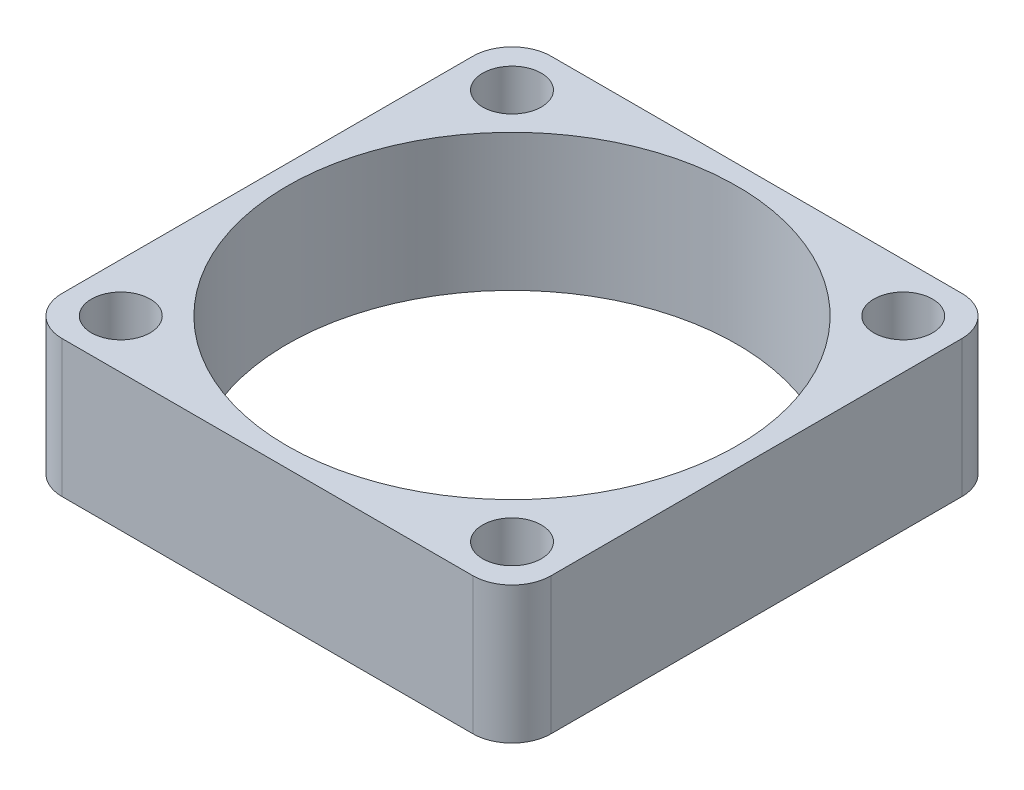
SolidWorks part; units mm, degrees
ref_plane "前视基准面" through (0, 0, 0) normal (0, 0, 1) x (1, 0, 0)
ref_plane "上视基准面" through (0, 0, 0) normal (0, 1, 0) x (1, 0, 0)
ref_plane "右视基准面" through (0, 0, 0) normal (1, 0, 0) x (0, 0, -1)
sketch "草图1" plane through (0, 0, 0) normal (0, 1, 0) x (1, 0, 0)
  line L1 (-12.5, -12.5) -> (12.5, -12.5)
  line L2 (-12.5, -12.5) -> (-12.5, 12.5)
  line L3 (-12.5, 12.5) -> (12.5, 12.5)
  line L4 (12.5, -12.5) -> (12.5, 12.5)
  line L5 (-12.5, -12.5) -> (12.5, 12.5) construction
  line L6 (-12.5, 12.5) -> (12.5, -12.5) construction
  circle A0 centre (-10, -10) radius 1.5
  circle A1 centre (10, -10) radius 1.5
  circle A2 centre (10, 10) radius 1.5
  circle A3 centre (-10, 10) radius 1.5
  point P0 (0, 0)
  point P8 (0, 0)
  point P10 (-9.8111, 3.3887)
  point P16 (0, 0)
  point P17 (0, 0)
  point P18 (0, 0)
  point P19 (13.7205, -4.7963)
  point P20 (0, 0)
  point P21 (-8.9786, 8.9786)
  dimension "D3" = 3
  dimension "D1" = 25
  dimension "D2" = 25
  dimension "D6" = 20
  dimension "D4" = 2
  dimension "D5" = 2
extrude "凸台-拉伸1" add sketch "草图1" along normal blind 7
fillet "圆角1" radius 2 4 edges at (12.5, 3.5, -12.5) (-12.5, 3.5, -12.5) (-12.5, 3.5, 12.5) (12.5, 3.5, 12.5)
sketch "草图2" plane through (0, 7, 0) normal (0, 1, 0) x (1, 0, 0)
  line L1 (-10.5, -12.5) -> (10.5, -12.5) construction
  circle A0 centre (0, 0) radius 11.5
  dimension "D1" = 1
extrude "切除-拉伸1" cut sketch "草图2" against normal blind 7
